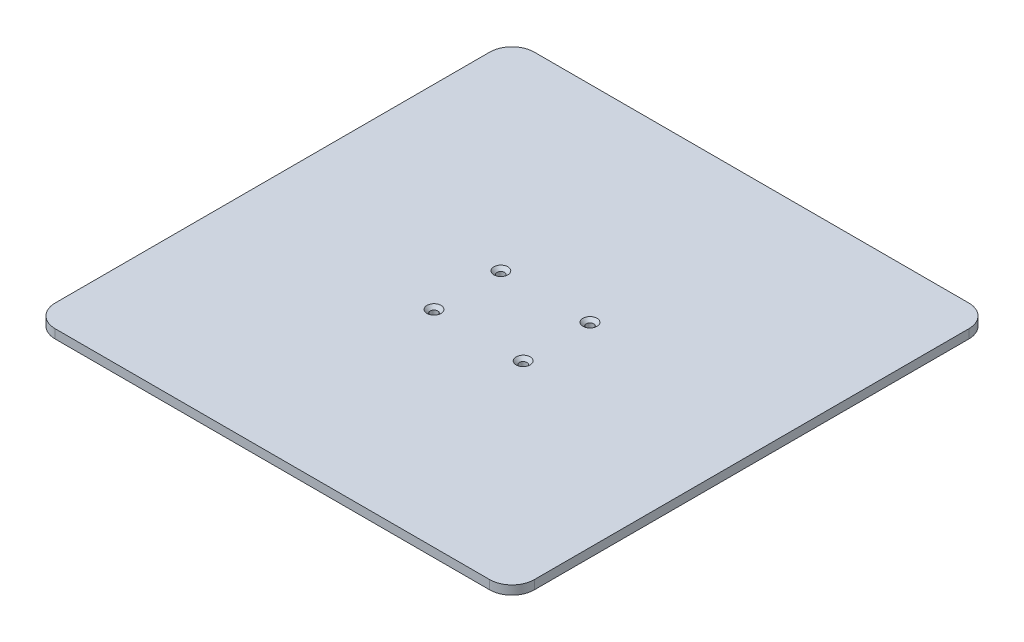
SolidWorks part; units mm, degrees
ref_plane "Front Plane" through (0, 0, 0) normal (0, 0, 1) x (1, 0, 0)
ref_plane "Top Plane" through (0, 0, 0) normal (0, 1, 0) x (1, 0, 0)
ref_plane "Right Plane" through (0, 0, 0) normal (1, 0, 0) x (0, 0, -1)
sketch "Sketch1" plane through (0, 0, 0) normal (0, 1, 0) x (1, 0, 0)
  line L1 (-107.5, -107.5) -> (107.5, -107.5)
  line L2 (-107.5, -107.5) -> (-107.5, 107.5)
  line L3 (-107.5, 107.5) -> (107.5, 107.5)
  line L4 (107.5, -107.5) -> (107.5, 107.5)
  line L5 (-107.5, -107.5) -> (107.5, 107.5) construction
  line L6 (-107.5, 107.5) -> (107.5, -107.5) construction
  point P0 (0, 0)
  dimension "D1" = 215
extrude "Boss-Extrude1" add sketch "Sketch1" along normal mid plane 4
sketch "Sketch2" plane through (0, 2, 0) normal (0, 1, 0) x (1, 0, 0)
  line L1 (-20, -15) -> (20, -15) construction
  line L2 (-20, -15) -> (-20, 15) construction
  line L3 (-20, 15) -> (20, 15) construction
  line L4 (20, -15) -> (20, 15) construction
  line L5 (-20, -15) -> (20, 15) construction
  line L6 (-20, 15) -> (20, -15) construction
  point P0 (0, 0)
  dimension "D1" = 40
  dimension "D2" = 30
hole_wizard "CSK for M3 Flat Head Machine Screw1" positions "Sketch3" profile "Sketch4" countersink size "M3" standard "ANSI Metric" end condition up to next
sketch "Sketch3" plane through (0, 2, 0) normal (0, 1, 0) x (1, 0, 0)
  point P0 (-20, 15)
  point P3 (20, 15)
  point P6 (20, -15)
  point P9 (-20, -15)
sketch "Sketch4" plane through (-20, 2, -15) normal (1, 0, 0) x (0, 0, 1)
  line L0 (0, 0) -> (0, 4)
  line L1 (0, 4) -> (1.7, 4)
  line L2 (1.7, 4) -> (1.7, 1.45)
  line L3 (1.7, 1.45) -> (3.15, 0)
  line L5 (3.15, 0) -> (0, 0)
  line L6 (-1.7, 1.45) -> (-3.15, 0) construction
  line L11 (0, -6.35) -> (0, 107.95) construction
  dimension "Thru Hole Dia." = 3.4
  dimension "Thru Hole Depth" = 4
  dimension "Near C'Sink Dia." = 6.3
  dimension "Near C'Sink Angle" = 90
fillet "Fillet1" radius 10 4 edges at (-107.5, 0, 107.5) (107.5, 0, 107.5) (107.5, 0, -107.5) (-107.5, 0, -107.5)
